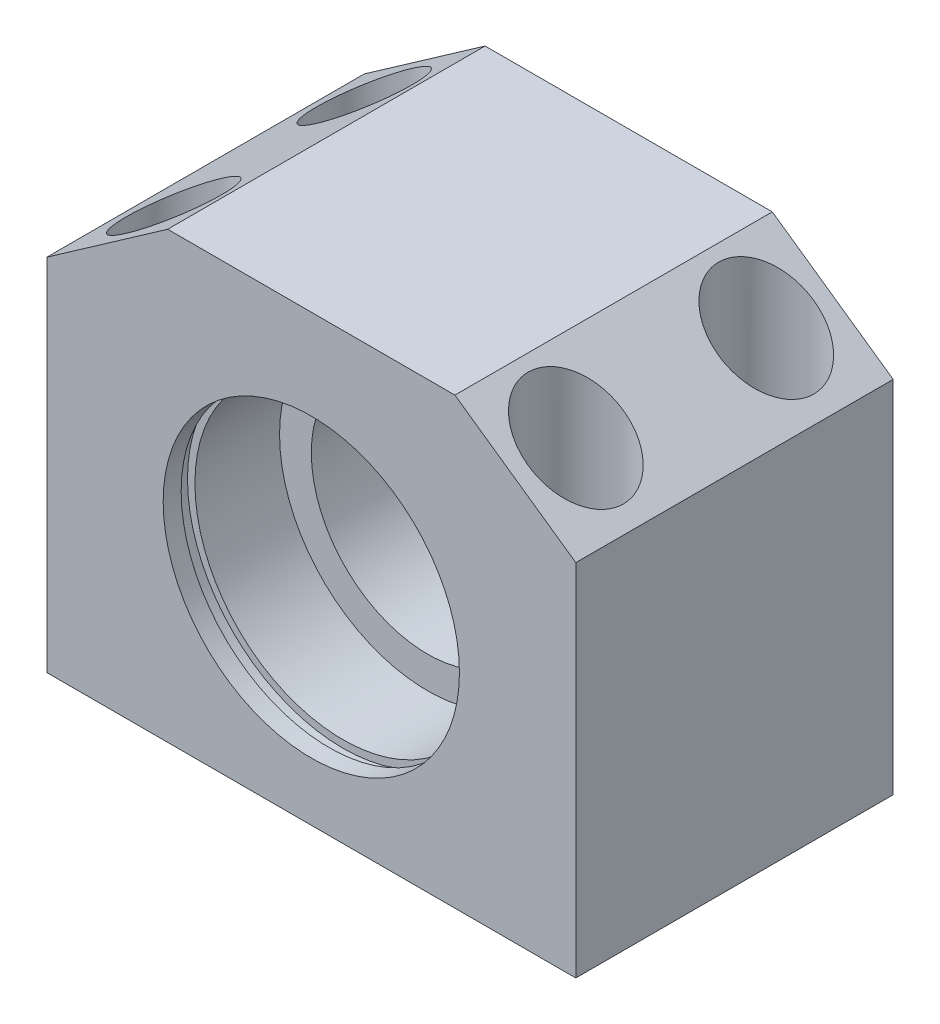
SolidWorks part; units mm, degrees
material "1.0037 (S235JR)"
ref_plane "Płaszczyzna przednia" through (0, 0, 0) normal (0, 0, 1) x (1, 0, 0)
ref_plane "Płaszczyzna górna" through (0, 0, 0) normal (0, 1, 0) x (1, 0, 0)
ref_plane "Płaszczyzna prawa" through (0, 0, 0) normal (1, 0, 0) x (0, 0, -1)
sketch "Szkic1" plane through (0, 0, 0) normal (0, 1, 0) x (1, 0, 0)
  line L1 (-25, -15) -> (25, -15)
  line L2 (-25, -15) -> (-25, 15)
  line L3 (-25, 15) -> (25, 15)
  line L4 (25, -15) -> (25, 15)
  line L5 (-25, -15) -> (25, 15) construction
  line L6 (-25, 15) -> (25, -15) construction
  point P0 (0, 0)
  dimension "D1" = 30
  dimension "D2" = 50
extrude "Dodanie-wyciągnięcie1" add sketch "Szkic1" along normal blind 42
sketch "Szkic3" plane through (0, 0, 15) normal (0, 0, 1) x (1, 0, 0)
  line L0 (0, 42) -> (0, 0) construction
  line L1 (-25, 42) -> (25, 42) construction
  line L2 (-25, 0) -> (25, 0) construction
  circle A0 centre (0, 19.5) radius 11
  dimension "D1" = 22
  dimension "D2" = 19.5
extrude "Wytnij-wyciągnięcie2" cut sketch "Szkic3" against normal through all
sketch "Szkic4" plane through (0, 0, 15) normal (0, 0, 1) x (1, 0, 0)
  circle A0 centre (0, 19.5) radius 14
  dimension "D1" = 28
extrude "Wytnij-wyciągnięcie3" cut sketch "Szkic4" against normal blind 11
sketch "Szkic5" plane through (0, 0, 0) normal (1, 0, 0) x (0, 0, -1)
  line L0 (-15, 5.5) -> (-4, 5.5) construction
  line L1 (-12, 5.5) -> (-13.3, 5.5)
  line L2 (-12, 5.5) -> (-12, 4.8)
  line L3 (-12, 4.8) -> (-13.3, 4.8)
  line L4 (-13.3, 5.5) -> (-13.3, 4.8)
  line L6 (-9.2946, 19.5) -> (-18.2923, 19.5) construction
  line L7 (-15, 33.5) -> (-15, 5.5) construction
  dimension "D1" = 1.3
  dimension "D2" = 14.7
  dimension "D3" = 3
  dimension "D4" = 19.5
sketch "Szkic6" plane through (0, 42, 0) normal (0, 1, 0) x (1, 0, 0)
  line L10 (19, -9) -> (19, 9)
  line L11 (19, 9) -> (-19, 9)
  line L12 (-19, 9) -> (-19, -9)
  line L13 (-19, -9) -> (19, -9)
  line L14 (19, -9) -> (19, 9)
  line L15 (19, 9) -> (-19, 9)
  line L16 (-19, 9) -> (-19, -9)
  line L17 (-19, -9) -> (19, -9)
  dimension "D1" = 6
hole_wizard "Pogłębienie walcowe pod M5 Wkręt do części metalowych z łbem sześciokątnym1" positions "Szkic8" profile "Szkic7" counterbore size "M5" standard "Ansi Metric" end condition through all
sketch "Szkic8" plane through (0, 42, 0) normal (0, 1, 0) x (1, 0, 0)
  point P0 (19, 9)
  point P3 (19, -9)
  point P6 (-19, -9)
  point P9 (-19, 9)
sketch "Szkic7" plane through (19, 42, -9) normal (1, 0, 0) x (0, 0, 1)
  line L0 (0, 0) -> (0, 42)
  line L1 (0, 42) -> (2.75, 42)
  line L3 (2.75, 42) -> (2.75, 13)
  line L4 (2.75, 13) -> (4.5, 13)
  line L5 (4.5, 13) -> (4.5, 0)
  line L7 (4.5, 0) -> (0, 0)
  line L11 (0, -6.35) -> (0, 107.95) construction
  dimension "Średnica otworu na wylot" = 5.5
  dimension "Głębokość otworu na wylot" = 42
  dimension "Średnica pogłębienia walcowego" = 9
  dimension "Głębokość pogłębienia walcowego" = 13
revolve "Wycięcie-obrót1" cut sketch "Szkic5" angle 360 about L6
sketch "Szkic9" plane through (0, 0, 15) normal (0, 0, 1) x (1, 0, 0)
  line L0 (13.5748, 42) -> (25, 34)
  line L1 (-25, 42) -> (25, 42) construction
  line L2 (25, 42) -> (25, 0) construction
  line L3 (-25, 34) -> (-13.5748, 42)
  line L4 (-25, 42) -> (-25, 0) construction
  line M3 (25, 0) -> (25, 42)
  line M4 (25, 42) -> (-25, 42)
  line M5 (-25, 42) -> (-25, 0)
  dimension "D1" = 8
  dimension "D2" = 35
extrude "Wytnij-wyciągnięcie5" cut sketch "Szkic9" against normal through all contours L3 M5 M4 | L0 M4 M3
